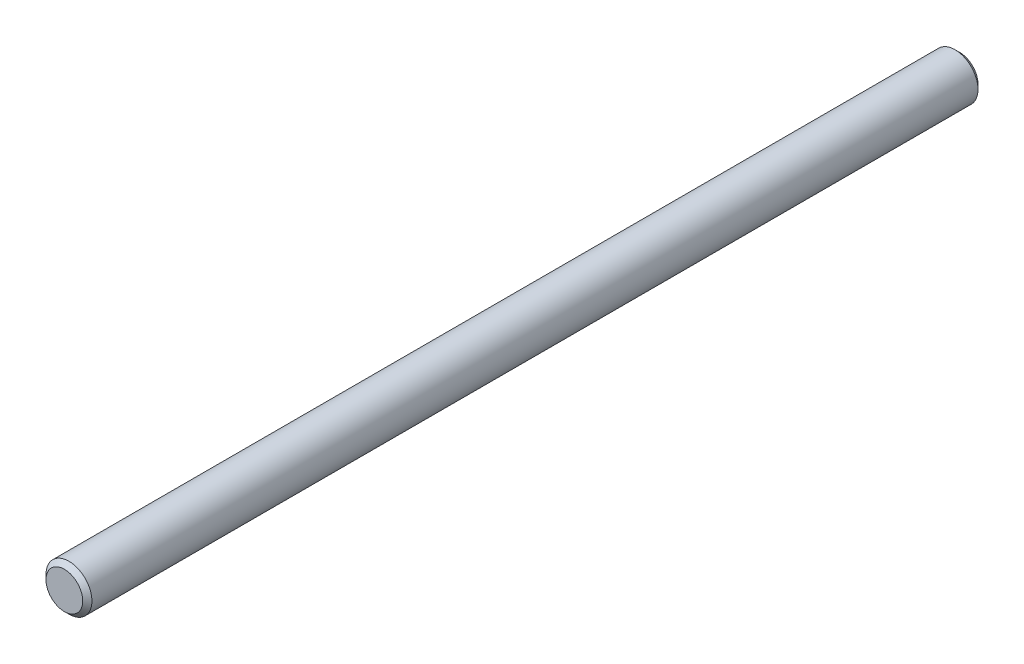
SolidWorks part; units mm, degrees
ref_plane "Front" through (0, 0, 0) normal (0, 0, 1) x (1, 0, 0)
ref_plane "Top" through (0, 0, 0) normal (0, 1, 0) x (1, 0, 0)
ref_plane "Right" through (0, 0, 0) normal (1, 0, 0) x (0, 0, -1)
sketch "Эскиз1" plane through (0, 0, 0) normal (0, 0, 1) x (1, 0, 0)
  circle A0 centre (0, 0) radius 0.5
  dimension "D1" = 1
extrude "Бобышка-Вытянуть1" add sketch "Эскиз1" along normal blind 19.5
chamfer "Фаска1" distance 0.1 angle 45 2 edges at (0.5, 0, 0) (0.5, 0, 19.5)
